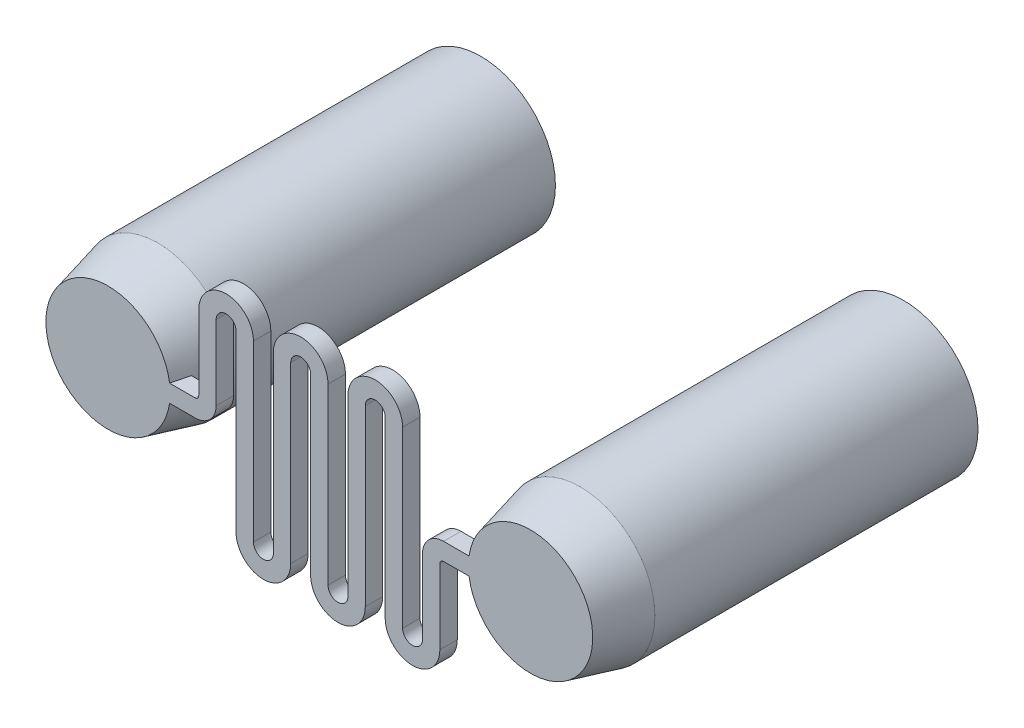
SolidWorks part; units mm, degrees
ref_plane "Front Plane" through (0, 0, 0) normal (0, 0, 1) x (1, 0, 0)
ref_plane "Top Plane" through (0, 0, 0) normal (0, 1, 0) x (1, 0, 0)
ref_plane "Right Plane" through (0, 0, 0) normal (1, 0, 0) x (0, 0, -1)
sketch "Sketch2" plane through (0, 0, 0) normal (0, 0, 1) x (1, 0, 0)
  line L3 (-20.5, -0.7) -> (-13.5, -0.7)
  line L6 (-11.8, 1) -> (-11.8, 7)
  line L9 (-10.2, 7) -> (-10.2, 0)
  line L12 (-10.2, 0) -> (-10.2, -7)
  line L15 (-5.8, -7) -> (-5.8, 0)
  line L18 (-5.8, 0) -> (-5.8, 7)
  line L21 (-4.2, 7) -> (-4.2, 0)
  line L22 (-4.2, 0) -> (-4.2, -7)
  line L23 (0.2, -7) -> (0.2, 0)
  line L24 (0.2, 0) -> (0.2, 7)
  line L25 (1.8, 7) -> (1.8, 0)
  line L26 (1.8, 0) -> (1.8, -7)
  line L27 (6.2, -7) -> (6.2, -1)
  line L28 (6.5, -0.7) -> (13.5, -0.7)
  line L29 (-20.5, 0.7) -> (-13.5, 0.7)
  line L30 (-13.2, 1) -> (-13.2, 7)
  line L31 (-8.8, 7) -> (-8.8, 0)
  line L32 (-8.8, 0) -> (-8.8, -7)
  line L33 (-7.2, -7) -> (-7.2, 0)
  line L34 (-7.2, 0) -> (-7.2, 7)
  line L35 (-2.8, 7) -> (-2.8, 0)
  line L36 (-2.8, 0) -> (-2.8, -7)
  line L37 (-1.2, -7) -> (-1.2, 0)
  line L38 (-1.2, 0) -> (-1.2, 7)
  line L39 (3.2, 7) -> (3.2, 0)
  line L40 (3.2, 0) -> (3.2, -7)
  line L41 (4.8, -7) -> (4.8, -1)
  line L42 (6.5, 0.7) -> (13.5, 0.7)
  arc A8 (-11.8, 1) -> (-13.5, -0.7) centre (-13.5, 1) cw
  arc A9 (-11.8, 7) -> (-10.2, 7) centre (-11, 7) cw
  arc A10 (-10.2, -7) -> (-5.8, -7) centre (-8, -7) ccw
  arc A11 (-5.8, 7) -> (-4.2, 7) centre (-5, 7) cw
  arc A12 (-4.2, -7) -> (0.2, -7) centre (-2, -7) ccw
  arc A13 (0.2, 7) -> (1.8, 7) centre (1, 7) cw
  arc A14 (1.8, -7) -> (6.2, -7) centre (4, -7) ccw
  arc A15 (6.2, -1) -> (6.5, -0.7) centre (6.5, -1) cw
  arc A16 (-13.2, 1) -> (-13.5, 0.7) centre (-13.5, 1) cw
  arc A17 (-13.2, 7) -> (-8.8, 7) centre (-11, 7) cw
  arc A18 (-8.8, -7) -> (-7.2, -7) centre (-8, -7) ccw
  arc A19 (-7.2, 7) -> (-2.8, 7) centre (-5, 7) cw
  arc A20 (-2.8, -7) -> (-1.2, -7) centre (-2, -7) ccw
  arc A21 (-1.2, 7) -> (3.2, 7) centre (1, 7) cw
  arc A22 (3.2, -7) -> (4.8, -7) centre (4, -7) ccw
  arc A23 (4.8, -1) -> (6.5, 0.7) centre (6.5, -1) cw
  arc A24 (-20.5, 0.7) -> (-20.5, -0.7) centre (-20.5, 0) ccw
  arc A25 (13.5, -0.7) -> (13.5, 0.7) centre (13.5, 0) ccw
  point P4 (0, 0)
  point P32 (5.5, 0)
  point P35 (-12.5, 0)
  dimension "D14" = 8
extrude "Boss-Extrude1" add sketch "Sketch2" along normal blind 1.4
ref_plane "Plane1" through (0, 0, 0) normal (0, 1, 0) x (1, 0, 0)
sketch "Sketch3" plane through (0, 0, 0) normal (0, 1, 0) x (1, 0, 0)
  line L0 (-20.5, -1.4) -> (-25.5, -1.4)
  line L2 (-20.5, -1.4) -> (-20.5, 28.6)
  line L3 (-20.5, 28.6) -> (-26.5, 28.6)
  line L4 (-26.5, 28.6) -> (-26.5, 2.6)
  line L5 (-26.5, 2.6) -> (-25.5, -1.4)
  dimension "D1" = 5
  dimension "D3" = 30
  dimension "D4" = 6
revolve "Revolve1" add sketch "Sketch3" angle 360 about L2
ref_plane "Plane2" through (0, 0, 0) normal (0, 1, 0) x (1, 0, 0)
sketch "Sketch4" plane through (0, 0, 0) normal (0, 1, 0) x (1, 0, 0)
  line L0 (13.5, -1.4) -> (18.5, -1.4)
  line L2 (13.5, -1.4) -> (13.5, 28.6)
  line L3 (13.5, 28.6) -> (19.5, 28.6)
  line L4 (19.5, 28.6) -> (19.5, 2.6)
  line L5 (19.5, 2.6) -> (18.5, -1.4)
  dimension "D1" = 5
  dimension "D3" = 30
  dimension "D4" = 6
revolve "Revolve2" add sketch "Sketch4" angle 360 about L2
sketch "Sketch5" plane through (0, 0, -28.6) normal (0, 0, -1) x (-1, 0, 0)
  circle A0 centre (-13.5, 0) radius 5
  circle A1 centre (20.5, 0) radius 5
  dimension "D1" = 10
  dimension "D2" = 10
extrude "Cut-Extrude1" cut sketch "Sketch5" against normal blind 28
